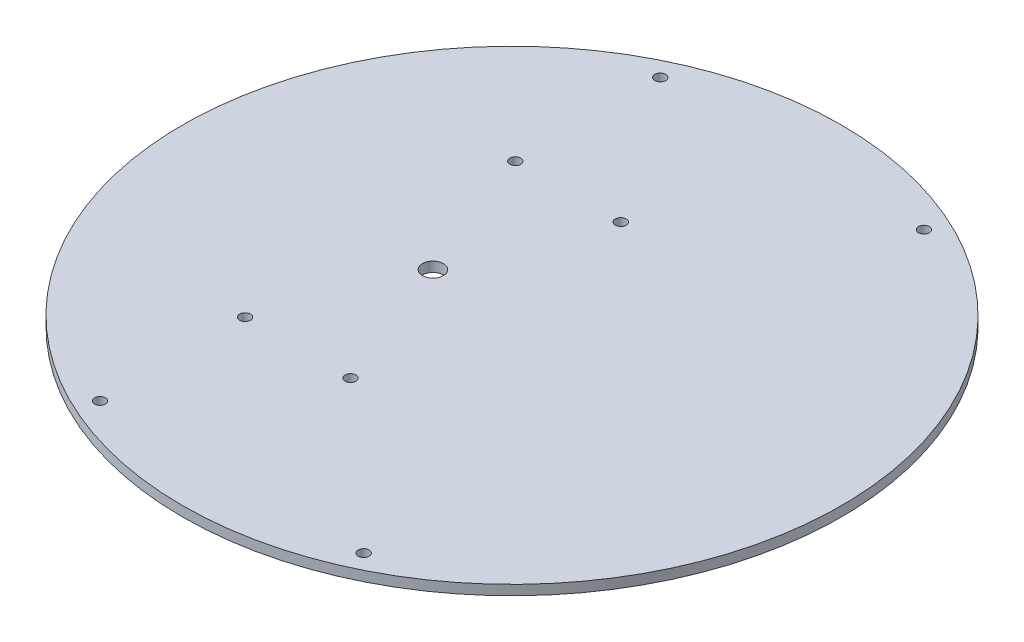
SolidWorks part; units mm, degrees
ref_plane "Alzado" through (0, 0, 0) normal (0, 0, 1) x (1, 0, 0)
ref_plane "Planta" through (0, 0, 0) normal (0, 1, 0) x (1, 0, 0)
ref_plane "Vista lateral" through (0, 0, 0) normal (1, 0, 0) x (0, 0, -1)
sketch "Croquis1" plane through (0, 0, 0) normal (0, 1, 0) x (1, 0, 0)
  line L0 (0, 0) -> (-88.4646, 0) construction
  line L1 (-88.4646, 0) -> (-72.2, -60.7004) construction
  line L5 (-88.4646, 0) -> (-88.4646, -58.7493) construction
  line L6 (-88.0486, -1.5529) -> (-71.8401, 49.51) construction
  line L8 (-72.2, 15.6777) -> (-72.2, -15.7875) construction
  line L10 (0, 0) -> (0, -71.6257) construction
  line L12 (72.2, 15.6777) -> (72.2, -15.7875) construction
  circle A15 centre (40, -85) radius 1.65
  circle A16 centre (40, 85) radius 1.65
  circle A19 centre (0, 0) radius 100
  circle A25 centre (-40, -85) radius 1.65
  circle A28 centre (-40, 85) radius 1.65
  circle A29 centre (-40, 41) radius 1.65
  circle A30 centre (-40, -41) radius 1.65
  circle A31 centre (-24, 0) radius 3.175
  circle A32 centre (-8, 41) radius 1.65
  circle A33 centre (-8, -41) radius 1.65
  point P17 (0, 0)
  point P72 (0, 0)
  dimension "D10" = 200
  dimension "D14" = 41
  dimension "D3" = 40
  dimension "D7" = 3.3
  dimension "D13" = 24
  dimension "D16" = 41
  dimension "D2" = 85
  dimension "D18" = 8
  dimension "D5" = 40
  dimension "D12" = 6.35
  dimension "D4" = 85
  dimension "D6" = 40
  dimension "D8" = 40
  dimension "D9" = 85
  dimension "D11" = 85
  dimension "D15" = 41
  dimension "D17" = 41
  dimension "D19" = 15
extrude "Saliente-Extruir1" add sketch "Croquis1" along normal blind 3
